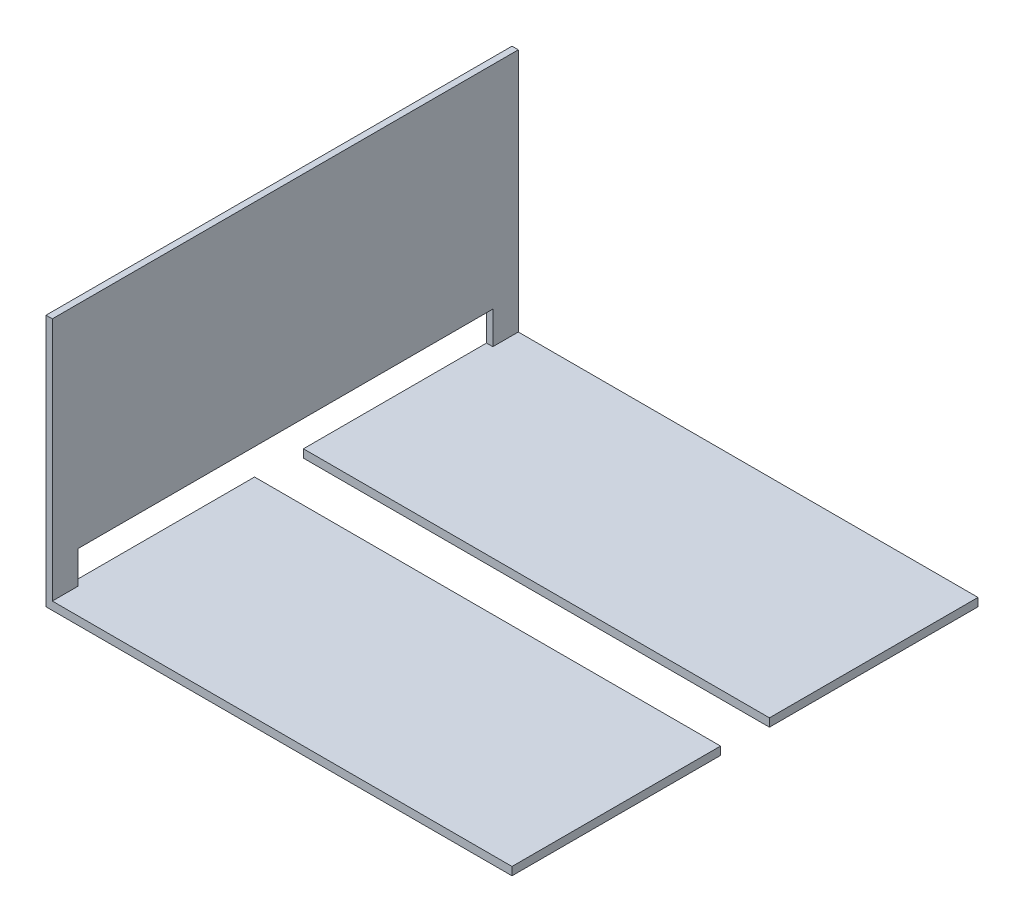
SolidWorks part; units mm, degrees
material "PBT General Purpose"
ref_plane "Front Plane" through (0, 0, 0) normal (0, 0, 1) x (1, 0, 0)
ref_plane "Top Plane" through (0, 0, 0) normal (0, 1, 0) x (1, 0, 0)
ref_plane "Right Plane" through (0, 0, 0) normal (1, 0, 0) x (0, 0, -1)
sketch "Sketch1" plane through (0, 0, 0) normal (0, 1, 0) x (1, 0, 0)
  line L1 (-143, -143) -> (143, -143)
  line L2 (-143, -143) -> (-143, 143)
  line L3 (-143, 143) -> (143, 143)
  line L4 (143, -143) -> (143, 143)
  line L5 (-143, -143) -> (143, 143) construction
  line L6 (-143, 143) -> (143, -143) construction
  point P0 (0, 0)
  dimension "D1" = 286
  dimension "D2" = 286
extrude "Boss-Extrude1" add sketch "Sketch1" along normal blind 5
sketch "Sketch4" plane through (0, 0, 0) normal (0, -1, 0) x (-1, 0, 0)
  circle A0 centre (132.5735, -80.9812) radius 2.4999
  circle A1 centre (132.5735, -36.9812) radius 2.5
  circle A2 centre (132.5696, 36.9812) radius 2.4999
  circle A3 centre (132.5696, 80.9812) radius 2.4999
extrude "Cut-Extrude1" cut sketch "Sketch4" against normal blind 4
sketch "Sketch5" plane through (0, 5, 0) normal (0, 1, 0) x (1, 0, 0)
  line L0 (-143, 143) -> (-143, -143) construction
  line L1 (143, 15) -> (-143, 15)
  line L2 (143, 15) -> (143, -15)
  line L3 (143, -15) -> (-143, -15)
  line L4 (-143, 15) -> (-143, -15)
  line L5 (143, 15) -> (-143, -15) construction
  line L6 (143, -15) -> (-143, 15) construction
  point P0 (0, 0)
  dimension "D1" = 30
extrude "Cut-Extrude2" cut sketch "Sketch5" against normal through all
sketch "Sketch6" plane through (0, 5, 0) normal (0, 1, 0) x (1, 0, 0)
  line L0 (143, 143) -> (-143, 143) construction
  line L1 (-143, -143) -> (-139.1236, -143)
  line L2 (-143, -143) -> (-143, 143)
  line L3 (-143, 143) -> (-139.1236, 143)
  line L4 (-139.1236, -143) -> (-139.1236, 143)
extrude "Boss-Extrude2" add sketch "Sketch6" along normal blind 150
sketch "Sketch7" plane through (-139.1236, 0, 0) normal (1, 0, 0) x (0, 0, -1)
  line L0 (-143, 5) -> (-15, 5) construction
  line L1 (127.3704, 25) -> (-127.3704, 25)
  line L3 (127.3704, 5) -> (-127.3704, 5)
  line L4 (-127.3704, 25) -> (-127.3704, 5)
  line L6 (-143, 155) -> (-143, 5) construction
  line L7 (127.3704, 25) -> (127.3704, 5)
  dimension "D1" = 15.6296
  dimension "D2" = 20
extrude "Cut-Extrude3" cut sketch "Sketch7" against normal through all
